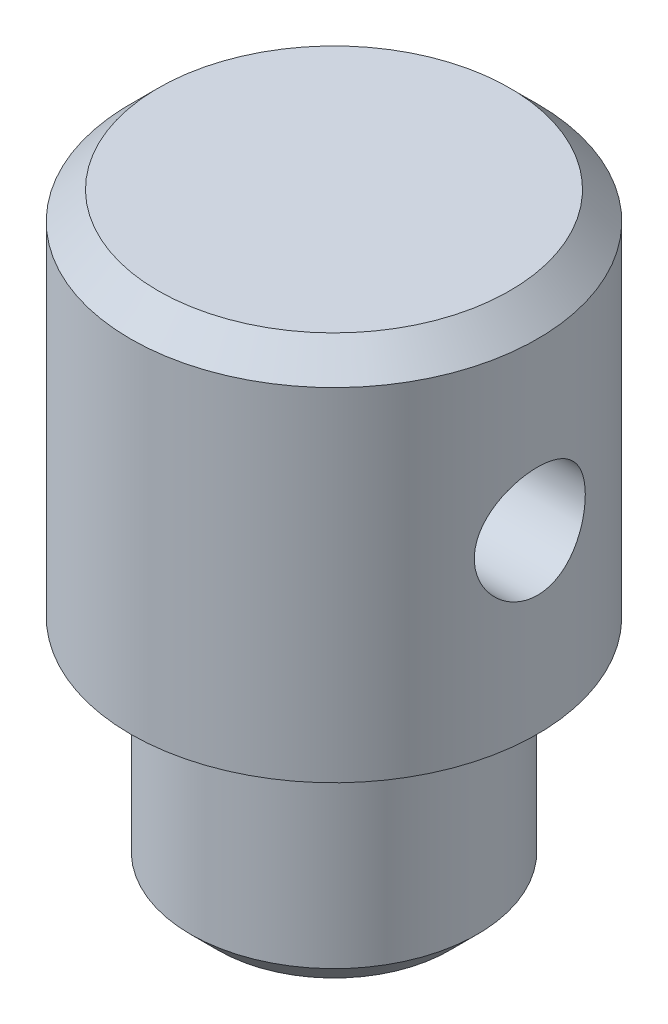
SolidWorks part; units mm, degrees
material "Brass"
ref_plane "Front" through (0, 0, 0) normal (0, 0, 1) x (1, 0, 0)
ref_plane "Top" through (0, 0, 0) normal (0, 1, 0) x (1, 0, 0)
ref_plane "Right" through (0, 0, 0) normal (1, 0, 0) x (0, 0, -1)
sketch "Sketch1" plane through (0, 0, 0) normal (0, 0, 1) x (1, 0, 0)
  line L0 (0, 0) -> (0, 16.51)
  line L1 (0, 16.51) -> (4.826, 16.51)
  line L2 (5.588, 15.748) -> (5.588, 6.35)
  line L3 (5.588, 6.35) -> (3.937, 6.35)
  line L4 (3.937, 6.35) -> (3.937, 0)
  line L5 (3.937, 0) -> (0, 0)
  line L6 (0, 0) -> (0, -11.1306) construction
  line L7 (4.826, 16.51) -> (5.588, 15.748)
  point P4 (5.588, 16.51)
  dimension "D1" = 7.874
  dimension "D2" = 0.762
  dimension "D3" = 45
  dimension "D4" = 15.748
  dimension "D5" = 6.35
  dimension "D6" = 11.176
revolve "Revolve1" add sketch "Sketch1" angle 360 about L6
hole_wizard "#18 (0.1695) Diameter Hole1" positions "Sketch3" profile "Sketch2" hole size "#18" standard "Ansi Inch"
sketch "Sketch3" plane through (0, 0, 0) normal (0, -1, 0) x (1, 0, 0)
  point P1 (0, 0)
sketch "Sketch2" plane through (0, 0, 0) normal (1, 0, 0) x (0, 0, -1)
  line L0 (0, 0) -> (0, 12.4694)
  line L1 (0, 12.4694) -> (2.1526, 11.176)
  line L2 (2.1526, 11.176) -> (2.1526, 0)
  line L5 (2.1526, 0) -> (0, 0)
  line L10 (0, 12.4694) -> (-2.1527, 11.176) construction
  line L11 (0, -6.35) -> (0, 107.95) construction
  dimension "Hole Dia." = 4.3053
  dimension "Hole Depth" = 11.176
  dimension "Drill Angle" = 118
sketch "Sketch4" plane through (0, 0, 0) normal (1, 0, 0) x (0, 0, -1)
  line L0 (0, 0) -> (0, 11.176) construction
  line L1 (-5.588, 6.35) -> (5.588, 6.35) construction
  circle A0 centre (0, 11.176) radius 1.524
  dimension "D1" = 3.048
  dimension "D2" = 4.826
extrude "Cut-Extrude1" cut sketch "Sketch4" against normal mid plane 22.86
chamfer "Chamfer1" distance 0.762 angle 45 1 edges at (0, 0, 3.937)
